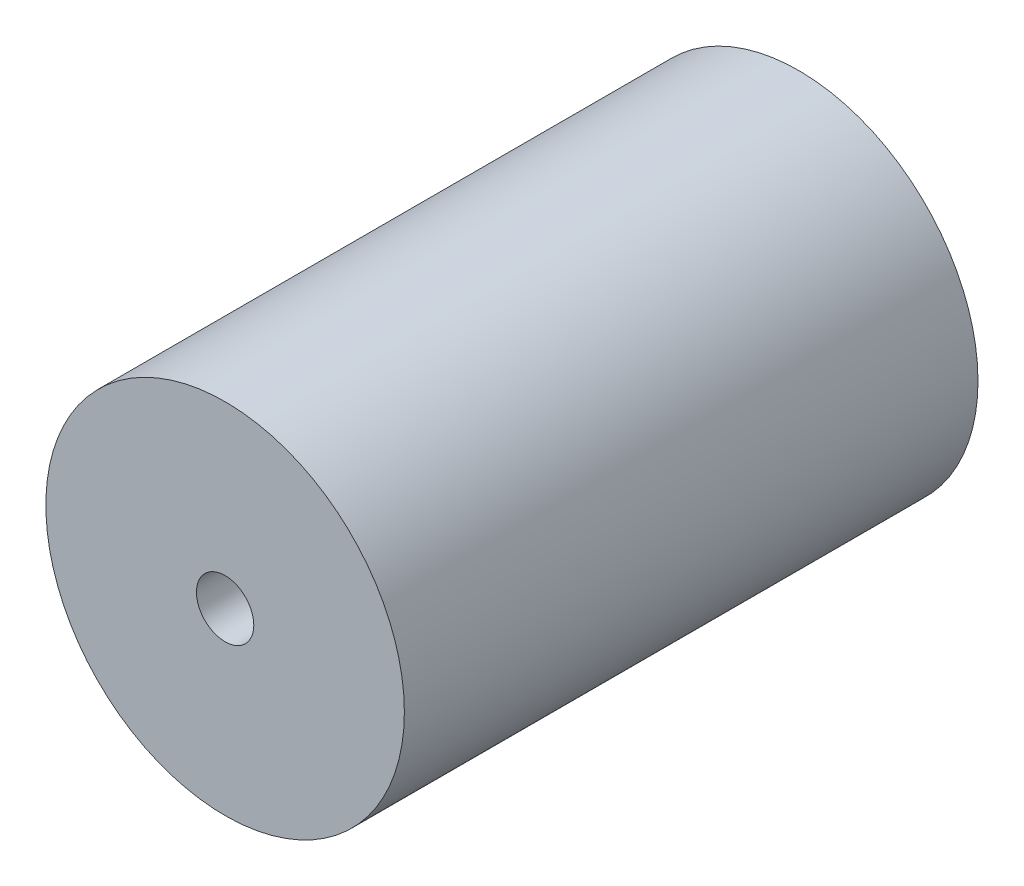
SolidWorks part; units mm, degrees
ref_plane "前视基准面" through (0, 0, 0) normal (0, 0, 1) x (1, 0, 0)
ref_plane "上视基准面" through (0, 0, 0) normal (0, 1, 0) x (1, 0, 0)
ref_plane "右视基准面" through (0, 0, 0) normal (1, 0, 0) x (0, 0, -1)
other "Configuration Table"
sketch "草图1" plane through (0, 0, 0) normal (0, 0, 1) x (1, 0, 0)
  circle A0 centre (0, 0) radius 2
  circle A1 centre (0, 0) radius 12.5
  dimension "D1" = 4
  dimension "D2" = 25
extrude "凸台-拉伸1" add sketch "草图1" along normal blind 40
